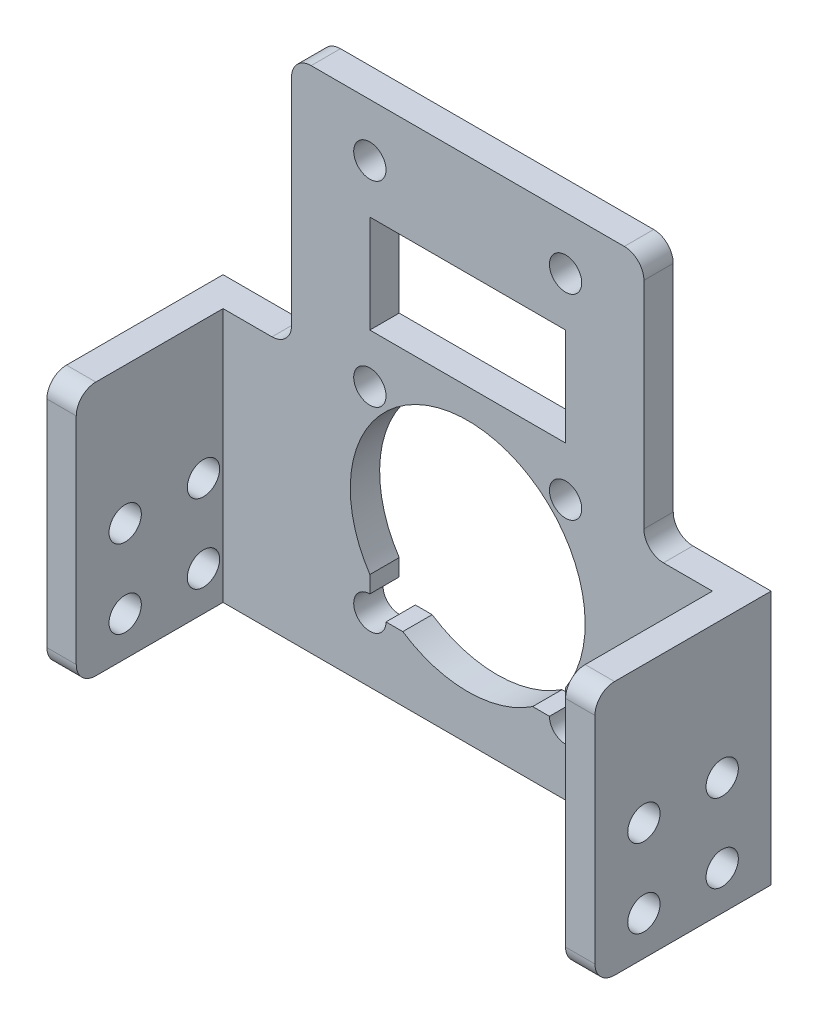
SolidWorks part; units mm, degrees
ref_plane "前视基准面" through (0, 0, 0) normal (0, 0, 1) x (1, 0, 0)
ref_plane "上视基准面" through (0, 0, 0) normal (0, 1, 0) x (1, 0, 0)
ref_plane "右视基准面" through (0, 0, 0) normal (1, 0, 0) x (0, 0, -1)
sketch "草图1" plane through (0, 0, 0) normal (0, 0, 1) x (1, 0, 0)
  line L0 (0, 26) -> (10, 26)
  line L1 (0, 0) -> (56, 0)
  line L2 (0, 0) -> (0, 26)
  line L3 (46, 26) -> (56, 26)
  line L4 (56, 0) -> (56, 26)
  line L5 (28, 52) -> (28, 0)
  line L6 (28, 6.6) -> (18, 6.6)
  line L7 (28, 6.6) -> (38, 6.6)
  line L8 (46, 26) -> (46, 52)
  line L9 (18, 6.6) -> (38, 6.6)
  line L10 (10, 26) -> (10, 52)
  line L11 (10, 52) -> (46, 52)
  line L12 (18, 6.6) -> (18, 46.6)
  line L13 (38, 6.6) -> (38, 46.6)
  line L14 (18, 46.6) -> (38, 46.6)
  line L15 (53, 26) -> (53, 0)
  line L16 (3, 26) -> (3, 0)
  line L19 (33, 41.6) -> (38, 41.6)
  line L20 (38, 41.6) -> (18, 41.6)
  line L21 (18, 41.6) -> (18, 31.6)
  line L22 (18, 31.6) -> (23, 31.6)
  line L23 (23, 31.6) -> (38, 31.6)
  circle A0 centre (18, 46.6) radius 1.65
  circle A1 centre (38, 46.6) radius 1.65
  circle A2 centre (18, 6.6) radius 1.65
  circle A3 centre (38, 6.6) radius 1.65
  circle A4 centre (18, 26.6) radius 1.65
  circle A5 centre (38, 26.6) radius 1.65
  circle A6 centre (28, 16.6) radius 12
extrude "凸台-拉伸4" add sketch "草图1" along normal blind 3 contours A6 L12 A4 A0 L14 L5 L11 L10 L0 L16 L1 L9 A2 | A6 L5 L1 L15 L3 L8 L11 L14 A1 L13 A5 A3 L9 | L3 L15 L1 L4 | L16 L0 L2 L1 | A6 L5 L23 L22 L12 A4 | A6 L13 A5 L23 L5 | A0 L12 L20 L5 L14 | A1 L14 L5 L20 L19 L13
sketch "草图2" plane through (0, 0, 3) normal (0, 0, 1) x (1, 0, 0)
  line L0 (0, 26) -> (0, 0)
  line L1 (0, 26) -> (3, 26)
  line L2 (0, 0) -> (3, 0)
  line L3 (3, 26) -> (3, 0)
  line L4 (56, 26) -> (56, 0)
  line L5 (56, 26) -> (53, 26)
  line L6 (56, 0) -> (53, 0)
  line L7 (53, 26) -> (53, 0)
extrude "凸台-拉伸5" add sketch "草图2" along normal blind 15
sketch "草图5" plane through (0, 0, 0) normal (-1, 0, 0) x (0, 0, 1)
  line L0 (0, 26) -> (18, 0)
  line L1 (18, 0) -> (18, 26)
  line L2 (18, 26) -> (9, 13)
  line L3 (9, 13) -> (0, 0)
  line L4 (4.5, 6.5) -> (13.5, 6.5)
  line L5 (9, 6.5) -> (9, 0)
  line L6 (18, 0) -> (0, 0) construction
  line L7 (5, 4) -> (13, 4)
  line L8 (9, 3.25) -> (9, 12)
  line L9 (13, 4) -> (13, 12)
  line L10 (9, 12) -> (13, 12)
  line L11 (9, 12) -> (9, 3.25)
  line L12 (9, 12) -> (5, 12)
  line L14 (5, 12) -> (5, 4)
  circle A0 centre (13, 12) radius 1.65
  circle A1 centre (5, 12) radius 1.65
  circle A2 centre (5, 4) radius 1.65
  circle A3 centre (13, 4) radius 1.65
extrude "切除-拉伸2" cut sketch "草图5" against normal blind 56 contours L12 A1 L14 | L14 A1 L12 | L9 A0 L10 | L10 A0 L9 | L14 A2 L7 | L7 A2 L14 | L9 A3 L7 | L7 A3 L9
fillet "圆角2" radius 2 8 edges at (46, 52, 1.5) (46, 26, 1.5) (10, 26, 1.5) (10, 52, 1.5) (54.5, 0, 18) (1.5, 0, 18) (54.5, 26, 18) (1.5, 26, 18)
